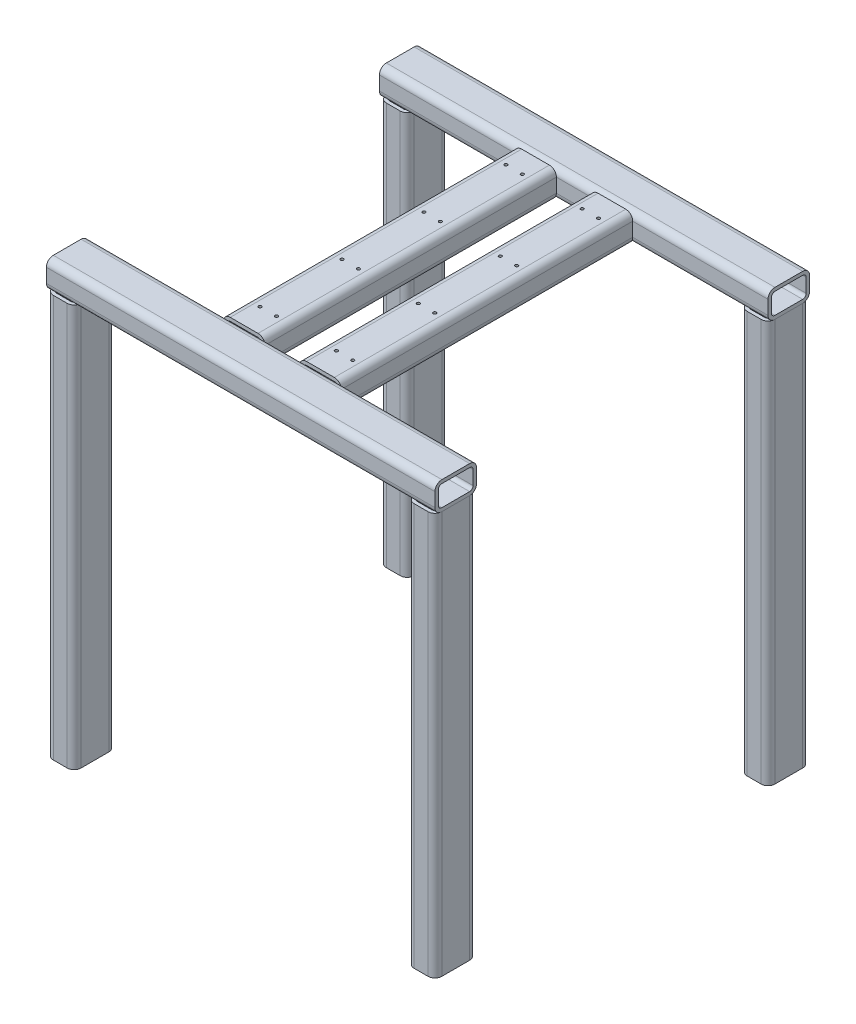
SolidWorks part; units mm, degrees
other "DetailItem1"
other "DetailItem2"
other "DetailItem3"
other "DetailItem4"
other "DetailItem5"
other "DetailItem6"
other "DetailItem7"
other "DetailItem9"
other "DetailItem10"
other "DetailItem11"
other "DetailItem12"
other "DetailItem13"
other "DetailItem14"
other "DetailItem15"
other "DetailItem16"
other "DetailItem17"
other "Weld Folder"
other "Weld Bead1"
other "Weld Bead2"
other "Weld Bead3"
other "Weld Bead4"
other "Weld Bead5"
other "Weld Bead6"
other "Weld Bead7"
other "Weld Bead9"
other "Weld Bead10"
other "Weld Bead11"
other "Weld Bead12"
other "Weld Bead13"
other "Weld Bead14"
other "Weld Bead15"
other "Weld Bead16"
other "Weld Bead17"
ref_plane "Front Plane" through (0, 0, 0) normal (0, 0, 1) x (1, 0, 0)
ref_plane "Top Plane" through (0, 0, 0) normal (0, 1, 0) x (1, 0, 0)
ref_plane "Right Plane" through (0, 0, 0) normal (1, 0, 0) x (0, 0, -1)
sketch3d "3DSketch1"
  line L13 (1529.2412, 0, 60.3935) -> (1529.2412, 762, 60.3935)
  line L14 (868.8412, 0, 60.3935) -> (868.8412, 762, 60.3935)
  line L15 (868.8412, 0, 669.9935) -> (868.8412, 762, 669.9935)
  line L16 (1529.2412, 0, 669.9935) -> (1529.2412, 762, 669.9935)
  line L17 (868.8412, 762, 60.3935) -> (1529.2412, 762, 60.3935)
  line L19 (1529.2412, 762, 669.9935) -> (868.8412, 762, 669.9935)
  line L21 (1129.1912, 762, 60.3935) -> (1129.1912, 762, 669.9935)
  line L23 (1268.8912, 762, 60.3935) -> (1268.8912, 762, 669.9935)
  point P9 (0, 0, 0)
  dimension "D1" = 660.4
  dimension "D2" = 609.6
  dimension "D3" = 762
  dimension "D4" = 260.35
  dimension "D5" = 260.35
  dimension "D8" = 260.35
  dimension "D9" = 260.35
other "Rectangular tube - configured 3 X 2 X 0.25(1)"
ref_plane "Plane1" through (868.8412, 762, 60.3935) normal (1, 0, 0) x (0, 1, 0)
sketch "Sketch1" plane through (868.8412, 762, 60.3935) normal (1, 0, 0) x (0, 1, 0)
  line L0 (-12.7, -31.75) -> (12.7, -31.75)
  line L1 (-19.05, -25.4) -> (-19.05, 25.4)
  line L2 (12.7, 31.75) -> (-12.7, 31.75)
  line L3 (19.05, 25.4) -> (19.05, -25.4)
  line L4 (-12.7, -38.1) -> (12.7, -38.1)
  line L5 (-25.4, -25.4) -> (-25.4, 25.4)
  line L6 (12.7, 38.1) -> (-12.7, 38.1)
  line L7 (25.4, 25.4) -> (25.4, -25.4)
  line L8 (0, 0) -> (25.4, 0) construction
  line L9 (0, 0) -> (0, 38.1) construction
  arc A0 (25.4, 25.4) -> (12.7, 38.1) centre (12.7, 25.4) ccw
  arc A1 (12.7, -38.1) -> (25.4, -25.4) centre (12.7, -25.4) ccw
  arc A2 (-25.4, -25.4) -> (-12.7, -38.1) centre (-12.7, -25.4) ccw
  arc A3 (-12.7, 38.1) -> (-25.4, 25.4) centre (-12.7, 25.4) ccw
  arc A4 (-12.7, 31.75) -> (-19.05, 25.4) centre (-12.7, 25.4) ccw
  arc A5 (19.05, 25.4) -> (12.7, 31.75) centre (12.7, 25.4) ccw
  arc A6 (12.7, -31.75) -> (19.05, -25.4) centre (12.7, -25.4) ccw
  arc A7 (-19.05, -25.4) -> (-12.7, -31.75) centre (-12.7, -25.4) ccw
  point P3 (0, -38.1)
  point P4 (-25.4, 0)
  point P5 (0, 0)
  point P6 (25.4, -38.1)
  point P7 (-25.4, -38.1)
  point P8 (-25.4, 38.1)
  point P33 (0, 0)
  point P35 (25.4, 38.1)
  point P36 (25.4, 0)
  point P37 (0, 38.1)
  dimension "D1" = 12.7
  dimension "Thickness" = 6.35
  dimension "V_leg" = 76.2
  dimension "H_leg" = 50.8
sketch "Sketch2" plane through (0, 787.4, 0) normal (0, 1, 0) x (1, 0, 0)
  line L0 (1243.4912, -631.8935) -> (1243.4912, -98.4935) construction
  line L1 (1103.7912, -631.8935) -> (1103.7912, -98.4935) construction
  line L2 (1294.2912, -633.7533) -> (1243.4912, -633.7533) construction
  line L4 (1103.7912, -633.7533) -> (1154.5912, -633.7533) construction
  circle A0 centre (1114.1912, -587.7533) radius 2.75
  circle A1 centre (1144.1912, -587.7533) radius 2.75
  circle A16 centre (1114.1912, -437.7533) radius 2.75
  circle A17 centre (1144.1912, -437.7533) radius 2.75
  circle A18 centre (1114.1912, -287.7533) radius 2.75
  circle A19 centre (1144.1912, -287.7533) radius 2.75
  circle A20 centre (1114.1912, -137.7533) radius 2.75
  circle A21 centre (1144.1912, -137.7533) radius 2.75
  circle A22 centre (1253.8912, -587.7533) radius 2.75
  circle A23 centre (1283.8912, -587.7533) radius 2.75
  circle A24 centre (1253.8912, -437.7533) radius 2.75
  circle A25 centre (1283.8912, -437.7533) radius 2.75
  circle A26 centre (1253.8912, -287.7533) radius 2.75
  circle A27 centre (1283.8912, -287.7533) radius 2.75
  circle A28 centre (1253.8912, -137.7533) radius 2.75
  circle A29 centre (1283.8912, -137.7533) radius 2.75
  point P8 (0, 0)
  point P9 (0, 0)
  point P18 (0, 0)
  point P34 (0, 0)
  point P35 (1144.1912, -594.7061)
  dimension "D1" = 5.5
  dimension "D2" = 30
  dimension "D4" = 46
  dimension "D5" = 5.5
  dimension "D8" = 5.5
  dimension "D10" = 5.5
  dimension "D14" = 5.5
  dimension "D16" = 5.5
  dimension "D19" = 5.5
  dimension "D21" = 5.5
  dimension "D3" = 10.4
  dimension "D6" = 30
  dimension "D7" = 150
  dimension "D9" = 30
  dimension "D11" = 30
  dimension "D12" = 150
  dimension "D13" = 150
  dimension "D15" = 30
  dimension "D17" = 30
  dimension "D18" = 150
  dimension "D20" = 30
  dimension "D22" = 30
  dimension "D23" = 150
  dimension "D24" = 150
  dimension "D25" = 10.4
  dimension "D26" = 46
extrude "Cut-Extrude1" cut sketch "Sketch2" against normal through all
